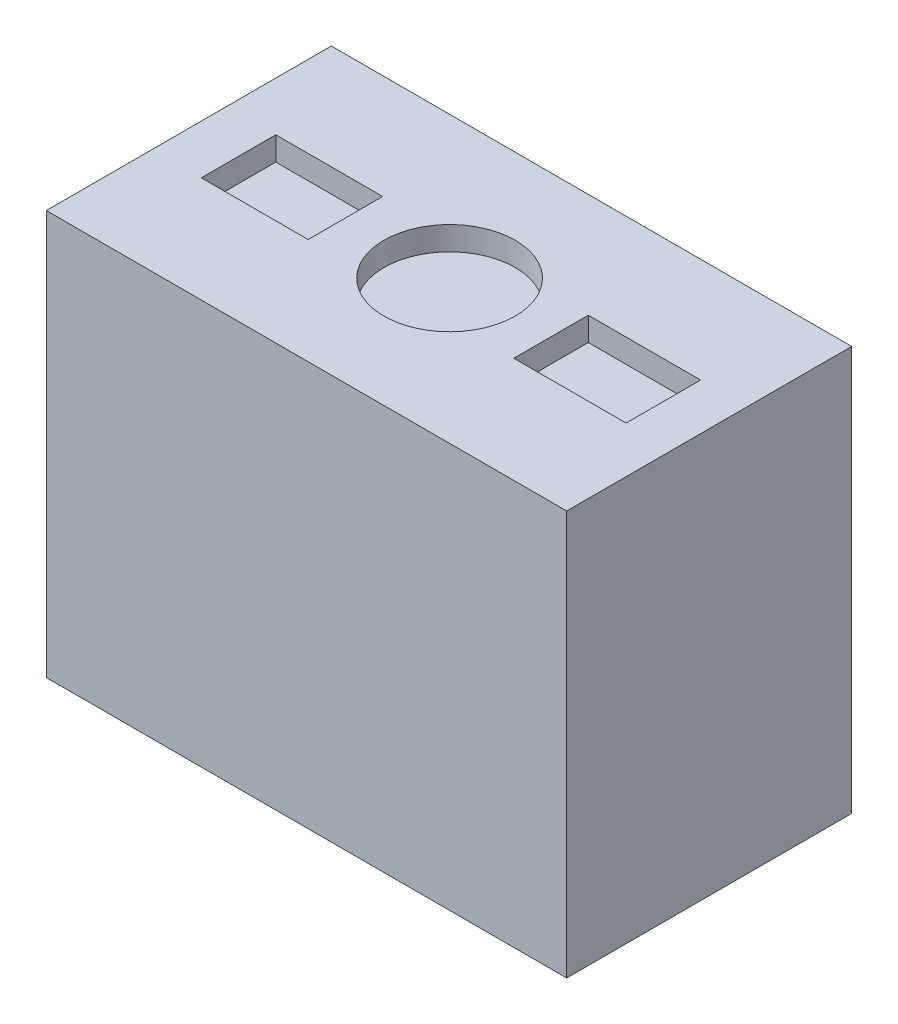
SolidWorks part; units mm, degrees
material "Custom Plastic"
ref_plane "Front Plane" through (0, 0, 0) normal (0, 0, 1) x (1, 0, 0)
ref_plane "Top Plane" through (0, 0, 0) normal (0, 1, 0) x (1, 0, 0)
ref_plane "Right Plane" through (0, 0, 0) normal (1, 0, 0) x (0, 0, -1)
sketch "Sketch1" plane through (0, 0, 0) normal (0, 0, 1) x (1, 0, 0)
  line L1 (-11, -8.55) -> (11, -8.55)
  line L2 (-11, -8.55) -> (-11, 8.55)
  line L3 (-11, 8.55) -> (11, 8.55)
  line L4 (11, -8.55) -> (11, 8.55)
  line L5 (-11, -8.55) -> (11, 8.55) construction
  line L6 (-11, 8.55) -> (11, -8.55) construction
  point P0 (0, 0)
extrude "Boss-Extrude1" add sketch "Sketch1" along normal blind 12.05
sketch "Sketch2" plane through (0, 0, 0) normal (0, 1, 0) x (1, 0, 0)
  line L1 (4.2901, -7.5746) -> (9.0366, -7.5746)
  line L2 (4.2901, -7.5746) -> (4.2901, -4.4254)
  line L3 (4.2901, -4.4254) -> (9.0366, -4.4254)
  line L4 (9.0366, -7.5746) -> (9.0366, -4.4254)
  line L5 (4.2901, -7.5746) -> (9.0366, -4.4254) construction
  line L6 (4.2901, -4.4254) -> (9.0366, -7.5746) construction
  line L7 (-8.9225, -7.5746) -> (-4.4042, -7.5746)
  line L8 (-8.9225, -7.5746) -> (-8.9225, -4.4254)
  line L9 (-8.9225, -4.4254) -> (-4.4042, -4.4254)
  line L10 (-4.4042, -7.5746) -> (-4.4042, -4.4254)
  line L11 (-8.9225, -7.5746) -> (-4.4042, -4.4254) construction
  line L12 (-8.9225, -4.4254) -> (-4.4042, -7.5746) construction
  circle A0 centre (0, -6) radius 2.7774
  point P2 (6.6634, -6)
  point P7 (-6.6634, -6)
extrude "Cut-Extrude1" cut sketch "Sketch2" against normal blind 1 from surface at 8.55 starting at face at (0, 8.55, 6.025)
